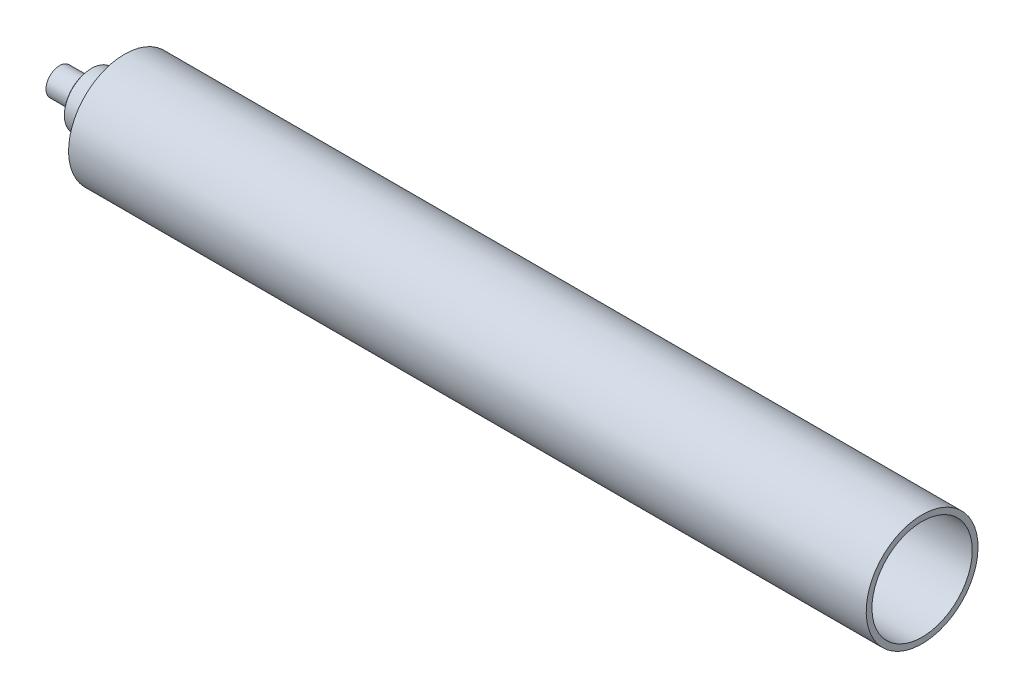
SolidWorks part; units mm, degrees
ref_plane "Front Plane" through (0, 0, 0) normal (0, 0, 1) x (1, 0, 0)
ref_plane "Top Plane" through (0, 0, 0) normal (0, 1, 0) x (1, 0, 0)
ref_plane "Right Plane" through (0, 0, 0) normal (1, 0, 0) x (0, 0, -1)
sketch "Sketch1" plane through (0, 0, 0) normal (0, 0, 1) x (1, 0, 0)
  line L0 (0, 0) -> (0, 11.938)
  line L1 (0, 11.938) -> (24.765, 11.938)
  line L2 (27.305, 14.478) -> (27.305, 22.933)
  line L3 (28.1044, 23.876) -> (57.15, 23.876)
  line L4 (57.15, 23.876) -> (57.15, 49.2125)
  line L5 (57.15, 49.2125) -> (759.206, 49.2125)
  line L6 (759.206, 49.2125) -> (759.206, 44.1325)
  line L7 (62.23, 0) -> (0, 0)
  line L8 (27.305, 22.933) -> (28.1044, 23.876)
  line L11 (62.23, 0) -> (62.23, 44.1325)
  line L12 (62.23, 44.1325) -> (759.206, 44.1325)
  arc A0 (24.765, 11.938) -> (27.305, 14.478) centre (24.765, 14.478) ccw
  point P11 (27.305, 11.938)
  dimension "D1" = 11.938
  dimension "D7" = 2.54
  dimension "D2" = 25.3365
  dimension "D3" = 49.2125
  dimension "D4" = 28.1044
  dimension "D5" = 27.305
  dimension "D6" = 702.056
  dimension "D8" = 57.15
  dimension "D9" = 22.933
  dimension "D10" = 5.08
  dimension "D11" = 5.08
revolve "Revolve1" add sketch "Sketch1" angle 360 about L7
sketch "Sketch16" plane through (0, 0, 0) normal (0, 1, 0) x (1, 0, 0)
  line L0 (0, 0) -> (0, 8.3503)
  line L1 (0, 8.3503) -> (1.905, 8.3503) construction
  line L2 (1.905, 8.3503) -> (1.905, 6.5564) construction
  line L3 (1.905, 6.5564) -> (0, 8.3503)
  line L4 (1.905, 6.5564) -> (1.905, 0)
  line L5 (-54.1337, 0) -> (54.1337, 0) construction
  line L6 (1.905, 0) -> (0, 0)
  dimension "D1" = 8.3503
  dimension "D2" = 6.5564
  dimension "D3" = 1.905
revolve "Cut-Revolve1" cut sketch "Sketch16" angle 360 about L6
sketch "Sketch19" plane through (1.905, 0, 0) normal (-1, 0, 0) x (0, 0, 1)
  circle A0 centre (0, 0) radius 4
  dimension "D1" = 8
extrude "Cut-Extrude3" cut sketch "Sketch19" against normal blind 25.4
sketch "Sketch32" plane through (0, 0, 0) normal (0, 1, 0) x (1, 0, 0)
  line L1 (-55, 0) -> (55, 0) construction
  line L2 (27.305, 0) -> (28.575, 0)
  line L3 (27.305, 0) -> (27.305, 6.3511)
  line L4 (27.305, 22.933) -> (27.305, -22.933) construction
  line L5 (27.305, 6.3511) -> (28.575, 0)
  dimension "D1" = 6.3511
  dimension "D2" = 1.27
  dimension "D3" = 27.305
revolve "Cut-Revolve6" cut sketch "Sketch32" angle 360 about L2
